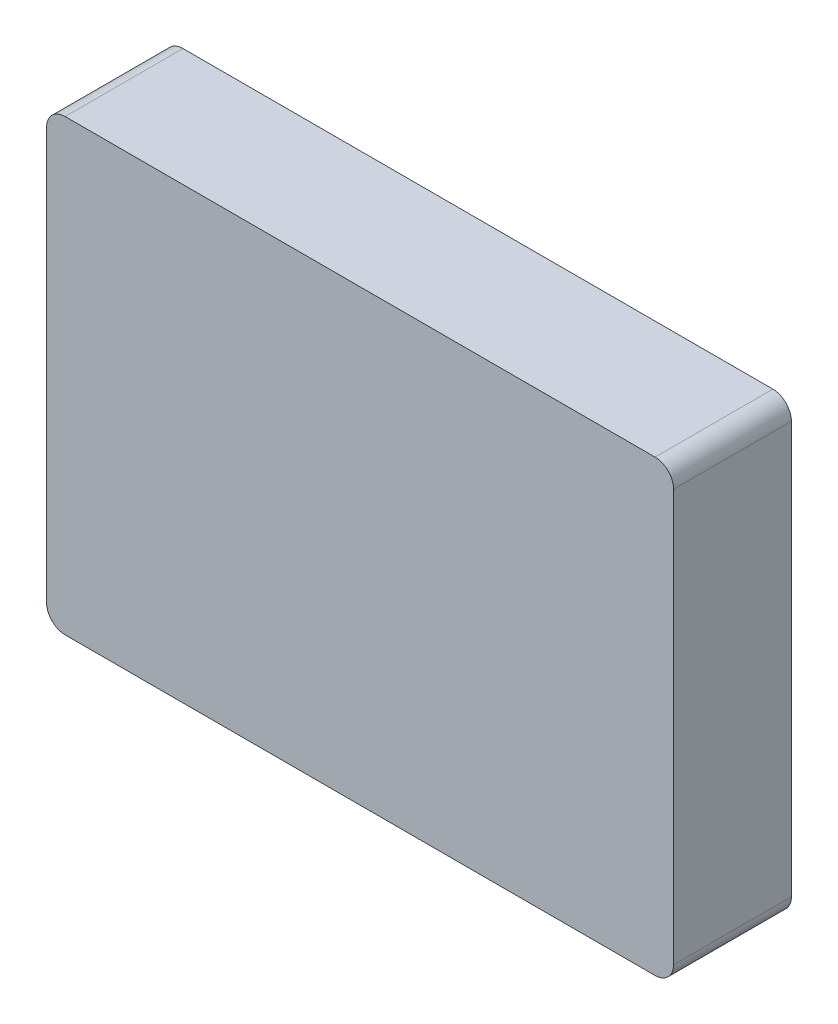
SolidWorks part; units mm, degrees
material "AISI 1045 Steel, cold drawn"
ref_plane "Front Plane" through (0, 0, 0) normal (0, 0, 1) x (1, 0, 0)
ref_plane "Top Plane" through (0, 0, 0) normal (0, 1, 0) x (1, 0, 0)
ref_plane "Right Plane" through (0, 0, 0) normal (1, 0, 0) x (0, 0, -1)
sketch "Sketch1" plane through (0, 0, 0) normal (0, 0, 1) x (1, 0, 0)
  line L1 (8.45, -6.05) -> (-8.45, -6.05)
  line L2 (8.45, -6.05) -> (8.45, 6.05)
  line L3 (8.45, 6.05) -> (-8.45, 6.05)
  line L4 (-8.45, -6.05) -> (-8.45, 6.05)
  line L5 (8.45, -6.05) -> (-8.45, 6.05) construction
  line L6 (8.45, 6.05) -> (-8.45, -6.05) construction
  point P0 (0, 0)
  dimension "D1" = 16.9
  dimension "D2" = 12.1
extrude "Boss-Extrude1" add sketch "Sketch1" along normal blind 3.175
fillet "Fillet1" radius 0.5 4 edges at (8.45, 6.05, 1.5875) (8.45, -6.05, 1.5875) (-8.45, -6.05, 1.5875) (-8.45, 6.05, 1.5875)
